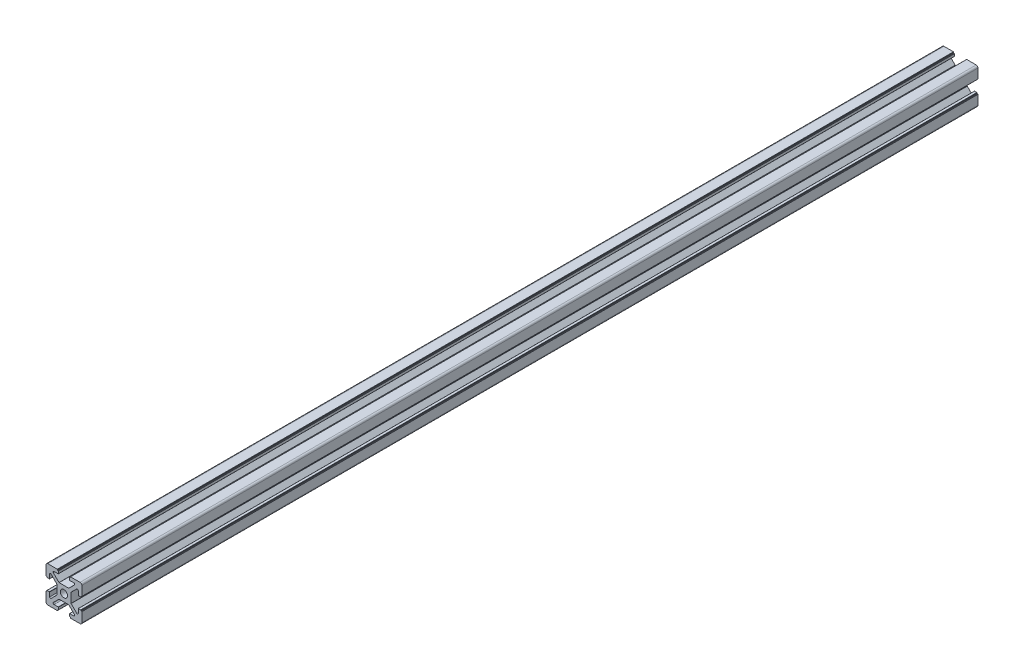
SolidWorks part; units mm, degrees
ref_plane "Plane1" through (0, 0, 0) normal (0, 0, 1) x (1, 0, 0)
ref_plane "Plane2" through (0, 0, 0) normal (0, 1, 0) x (1, 0, 0)
ref_plane "Plane3" through (0, 0, 0) normal (1, 0, 0) x (0, 0, -1)
sketch "Sketch1" plane through (0, 0, 0) normal (0, 0, 1) x (1, 0, 0)
  line L0 (-26.4662, 0) -> (25.1675, 0) construction
  line L1 (0, 16.7588) -> (0, -17.8201) construction
  line L2 (-10, 9) -> (-10, 3.7)
  line L3 (8, -5.5201) -> (8, -3.2)
  line L4 (-4, 0) -> (-4, 2.6858)
  line L5 (-2.6858, 4) -> (2.6858, 4)
  line L6 (4, 0) -> (4, 2.6858)
  line L7 (-4, -4) -> (4, 4) construction
  line L8 (-4, 4) -> (4, -4) construction
  line L9 (-9, 10) -> (-3.7, 10)
  line L10 (-8, 5.5201) -> (-8, 3.2)
  line L11 (10, -9) -> (10, -3.7)
  line L12 (9.6, -3.6) -> (9.9, -3.6)
  line L13 (-10, 10) -> (10, -10) construction
  line L14 (-10, -10) -> (10, 10) construction
  line L15 (9.5, -3.2) -> (9.5, -3.5)
  line L16 (8.1, -3.1) -> (9.4, -3.1)
  line L17 (-5.5201, 8) -> (-3.2, 8)
  line L18 (-7.1464, 5.8737) -> (-4.0293, 2.7565)
  line L19 (-5.8737, 7.1464) -> (-2.7565, 4.0293)
  line L20 (-3.1, 8.1) -> (-3.1, 9.4)
  line L21 (-3.2, 9.5) -> (-3.5, 9.5)
  line L22 (-3.6, 9.6) -> (-3.6, 9.9)
  line L23 (3.1, 8.1) -> (3.1, 9.4)
  line L24 (3.2, 9.5) -> (3.5, 9.5)
  line L25 (3.6, 9.6) -> (3.6, 9.9)
  line L26 (2.7565, 4.0293) -> (5.8737, 7.1464)
  line L27 (4.0293, 2.7565) -> (7.1464, 5.8737)
  line L28 (-8, 8) -> (8, 8) construction
  line L29 (-8, 8) -> (-8, -8) construction
  line L30 (8, 8) -> (8, -8) construction
  line L31 (3.7, 10) -> (9, 10)
  line L32 (-9, 10) -> (9, 10) construction
  line L33 (3.2, 8) -> (5.5201, 8)
  line L34 (-9.5, 3.2) -> (-9.5, 3.5)
  line L35 (-9.6, 3.6) -> (-9.9, 3.6)
  line L36 (-8.1, 3.1) -> (-9.4, 3.1)
  line L37 (-9, -10) -> (9, -10) construction
  line L38 (-10, 9) -> (-10, -9) construction
  line L39 (-8, -8) -> (8, -8) construction
  line L40 (10, 9) -> (10, -9) construction
  line L41 (8.1, 3.1) -> (9.4, 3.1)
  line L42 (9.5, 3.2) -> (9.5, 3.5)
  line L43 (9.6, 3.6) -> (9.9, 3.6)
  line L44 (10, 9) -> (10, 3.7)
  line L45 (8, 5.5201) -> (8, 3.2)
  line L46 (-8.1, -3.1) -> (-9.4, -3.1)
  line L47 (-9.6, -3.6) -> (-9.9, -3.6)
  line L48 (-9.5, -3.2) -> (-9.5, -3.5)
  line L49 (3.2, -8) -> (5.5201, -8)
  line L50 (3.7, -10) -> (9, -10)
  line L51 (4.0293, -2.7565) -> (7.1464, -5.8737)
  line L52 (2.7565, -4.0293) -> (5.8737, -7.1464)
  line L53 (3.6, -9.6) -> (3.6, -9.9)
  line L54 (3.2, -9.5) -> (3.5, -9.5)
  line L55 (3.1, -8.1) -> (3.1, -9.4)
  line L56 (-3.6, -9.6) -> (-3.6, -9.9)
  line L57 (-3.2, -9.5) -> (-3.5, -9.5)
  line L58 (-3.1, -8.1) -> (-3.1, -9.4)
  line L59 (-5.8737, -7.1464) -> (-2.7565, -4.0293)
  line L60 (-7.1464, -5.8737) -> (-4.0293, -2.7565)
  line L61 (-5.5201, -8) -> (-3.2, -8)
  line L62 (-8, -5.5201) -> (-8, -3.2)
  line L63 (-9, -10) -> (-3.7, -10)
  line L64 (-2.6858, -4) -> (2.6858, -4)
  line L65 (-10, -9) -> (-10, -3.7)
  line L66 (-4, 0) -> (-4, -2.6858)
  line L68 (4, 0) -> (4, -2.6858)
  circle A0 centre (0, 0) radius 2
  arc A1 (-10, 9) -> (-9, 10) centre (-9, 9) cw
  arc A2 (10, -3.7) -> (9.9, -3.6) centre (9.9, -3.7) ccw
  arc A3 (-10, -9) -> (-9, -10) centre (-9, -9) ccw construction
  arc A4 (10, 9) -> (9, 10) centre (9, 9) ccw
  arc A5 (-8, -8) -> (-8, -8) centre (-8, -8) ccw
  arc A6 (8, -8) -> (8, -8) centre (8, -8) cw
  arc A7 (8, 8) -> (8, 8) centre (8, 8) ccw
  arc A8 (-8, 8) -> (-8, 8) centre (-8, 8) cw
  arc A9 (-5.5201, 8) -> (-5.8737, 7.1464) centre (-5.5201, 7.5) ccw
  arc A10 (5.5201, 8) -> (5.8737, 7.1464) centre (5.5201, 7.5) cw
  arc A11 (-8, 5.5201) -> (-7.1464, 5.8737) centre (-7.5, 5.5201) cw
  arc A12 (8, 5.5201) -> (7.1464, 5.8737) centre (7.5, 5.5201) ccw
  arc A13 (-3.6, 9.9) -> (-3.7, 10) centre (-3.7, 9.9) ccw
  arc A14 (-3.5, 9.5) -> (-3.6, 9.6) centre (-3.5, 9.6) cw
  arc A15 (-3.2, 9.5) -> (-3.1, 9.4) centre (-3.2, 9.4) cw
  arc A16 (-3.1, 8.1) -> (-3.2, 8) centre (-3.2, 8.1) cw
  arc A17 (3.2, 8) -> (3.1, 8.1) centre (3.2, 8.1) cw
  arc A18 (3.2, 9.5) -> (3.1, 9.4) centre (3.2, 9.4) ccw
  arc A19 (3.5, 9.5) -> (3.6, 9.6) centre (3.5, 9.6) ccw
  arc A20 (3.7, 10) -> (3.6, 9.9) centre (3.7, 9.9) ccw
  arc A21 (-2.6858, 4) -> (-2.7565, 4.0293) centre (-2.6858, 4.1) cw
  arc A22 (-4, 2.6858) -> (-4.0293, 2.7565) centre (-4.1, 2.6858) ccw
  arc A23 (2.6858, 4) -> (2.7565, 4.0293) centre (2.6858, 4.1) ccw
  arc A24 (4.0293, 2.7565) -> (4, 2.6858) centre (4.1, 2.6858) ccw
  arc A25 (-9.5, 3.2) -> (-9.4, 3.1) centre (-9.4, 3.2) ccw
  arc A26 (-9.5, 3.5) -> (-9.6, 3.6) centre (-9.6, 3.5) ccw
  arc A27 (-9.9, 3.6) -> (-10, 3.7) centre (-9.9, 3.7) cw
  arc A28 (-8.1, 3.1) -> (-8, 3.2) centre (-8.1, 3.2) ccw
  arc A29 (8, 3.2) -> (8.1, 3.1) centre (8.1, 3.2) ccw
  arc A30 (9.5, 3.2) -> (9.4, 3.1) centre (9.4, 3.2) cw
  arc A31 (9.5, 3.5) -> (9.6, 3.6) centre (9.6, 3.5) cw
  arc A32 (10, 3.7) -> (9.9, 3.6) centre (9.9, 3.7) cw
  arc A33 (10, -9) -> (9, -10) centre (9, -9) cw construction
  arc A34 (9.5, -3.5) -> (9.6, -3.6) centre (9.6, -3.5) ccw
  arc A35 (9.5, -3.2) -> (9.4, -3.1) centre (9.4, -3.2) ccw
  arc A36 (8, -3.2) -> (8.1, -3.1) centre (8.1, -3.2) cw
  arc A37 (-8.1, -3.1) -> (-8, -3.2) centre (-8.1, -3.2) cw
  arc A38 (-9.9, -3.6) -> (-10, -3.7) centre (-9.9, -3.7) ccw
  arc A39 (-9.5, -3.5) -> (-9.6, -3.6) centre (-9.6, -3.5) cw
  arc A40 (-9.5, -3.2) -> (-9.4, -3.1) centre (-9.4, -3.2) cw
  arc A41 (4.0293, -2.7565) -> (4, -2.6858) centre (4.1, -2.6858) cw
  arc A42 (2.6858, -4) -> (2.7565, -4.0293) centre (2.6858, -4.1) cw
  arc A43 (-4, -2.6858) -> (-4.0293, -2.7565) centre (-4.1, -2.6858) cw
  arc A44 (-2.6858, -4) -> (-2.7565, -4.0293) centre (-2.6858, -4.1) ccw
  arc A45 (3.7, -10) -> (3.6, -9.9) centre (3.7, -9.9) cw
  arc A46 (3.5, -9.5) -> (3.6, -9.6) centre (3.5, -9.6) cw
  arc A47 (3.2, -9.5) -> (3.1, -9.4) centre (3.2, -9.4) cw
  arc A48 (3.2, -8) -> (3.1, -8.1) centre (3.2, -8.1) ccw
  arc A49 (-3.1, -8.1) -> (-3.2, -8) centre (-3.2, -8.1) ccw
  arc A50 (-3.2, -9.5) -> (-3.1, -9.4) centre (-3.2, -9.4) ccw
  arc A51 (-3.5, -9.5) -> (-3.6, -9.6) centre (-3.5, -9.6) ccw
  arc A52 (-3.6, -9.9) -> (-3.7, -10) centre (-3.7, -9.9) cw
  arc A53 (8, -5.5201) -> (7.1464, -5.8737) centre (7.5, -5.5201) cw
  arc A54 (-8, -5.5201) -> (-7.1464, -5.8737) centre (-7.5, -5.5201) ccw
  arc A55 (5.5201, -8) -> (5.8737, -7.1464) centre (5.5201, -7.5) ccw
  arc A56 (-5.5201, -8) -> (-5.8737, -7.1464) centre (-5.5201, -7.5) cw
  arc A57 (10, -9) -> (9, -10) centre (9, -9) cw
  arc A58 (-10, -9) -> (-9, -10) centre (-9, -9) ccw
  point P0 (0, 0)
  point P70 (3.1, 8.75)
  point P72 (-3.6, 10)
  point P75 (-3.6, 9.5)
  point P82 (3.1, 8)
  point P87 (3.6, 9.5)
  point P90 (3.6, 10)
  point P198 (3.6, -10)
  point P199 (3.6, -9.5)
  point P200 (3.1, -8)
  point P201 (-3.6, -9.5)
  point P202 (-3.6, -10)
extrude "Boss-Extrude1" add sketch "Sketch1" along normal blind 500 contours L65 A58 L63 A52 L56 A51 L57 A50 L58 A49 L61 A56 L59 A44 L64 A42 L52 A55 L49 A48 L55 A47 L54 A46 L53 A45 L50 A57 L11 A2 L12 A34 L15 A35 L16 A36 L3 A53 L51 A41 L68 L6 A24 L27 A12 L45 A29 L41 A30 L42 A31
